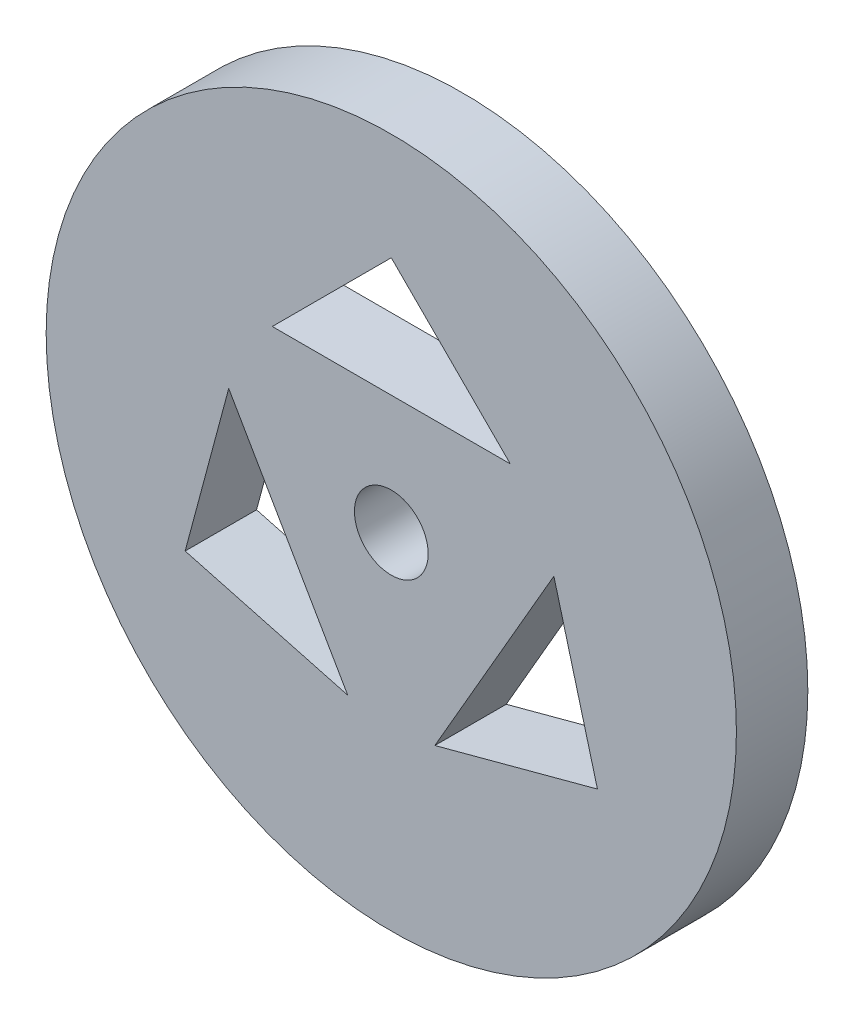
SolidWorks part; units mm, degrees
ref_plane "前视基准面" through (0, 0, 0) normal (0, 0, 1) x (1, 0, 0)
ref_plane "上视基准面" through (0, 0, 0) normal (0, 1, 0) x (1, 0, 0)
ref_plane "右视基准面" through (0, 0, 0) normal (1, 0, 0) x (0, 0, -1)
sketch "草图1" plane through (0, 0, 0) normal (0, 0, 1) x (1, 0, 0)
  circle A9 centre (0, 0) radius 29
  point P35 (0, 0)
  dimension "D2" = 58
extrude "凸台-拉伸1" add sketch "草图1" along normal blind 6
sketch "草图2" plane through (0, 0, 6) normal (0, 0, 1) x (1, 0, 0)
  circle A1 centre (0, 0) radius 3.1
  point P7 (0, 0)
  dimension "D1" = 6.2
extrude "切除-拉伸1" cut sketch "草图2" against normal through all
sketch "草图3" plane through (0, 0, 6) normal (0, 0, 1) x (1, 0, 0)
  line L0 (-20, 0) -> (20, 0) construction
  line L1 (0, 0) -> (0, 20) construction
  line L2 (-10, 10) -> (0, 20)
  line L3 (0, 20) -> (10, 10)
  line L4 (-10, 10) -> (10, 10)
  line L5 (13.6603, 3.6603) -> (17.3205, -10)
  line L6 (17.3205, -10) -> (3.6603, -13.6603)
  line L7 (13.6603, 3.6603) -> (3.6603, -13.6603)
  line L8 (-3.6603, -13.6603) -> (-17.3205, -10)
  line L9 (-17.3205, -10) -> (-13.6603, 3.6603)
  line L10 (-3.6603, -13.6603) -> (-13.6603, 3.6603)
  point P5 (0, 0)
  point P18 (0, 0)
  dimension "D1" = 20
  dimension "D2" = 40
  dimension "D3" = 3
extrude "切除-拉伸2" cut sketch "草图3" against normal through all
